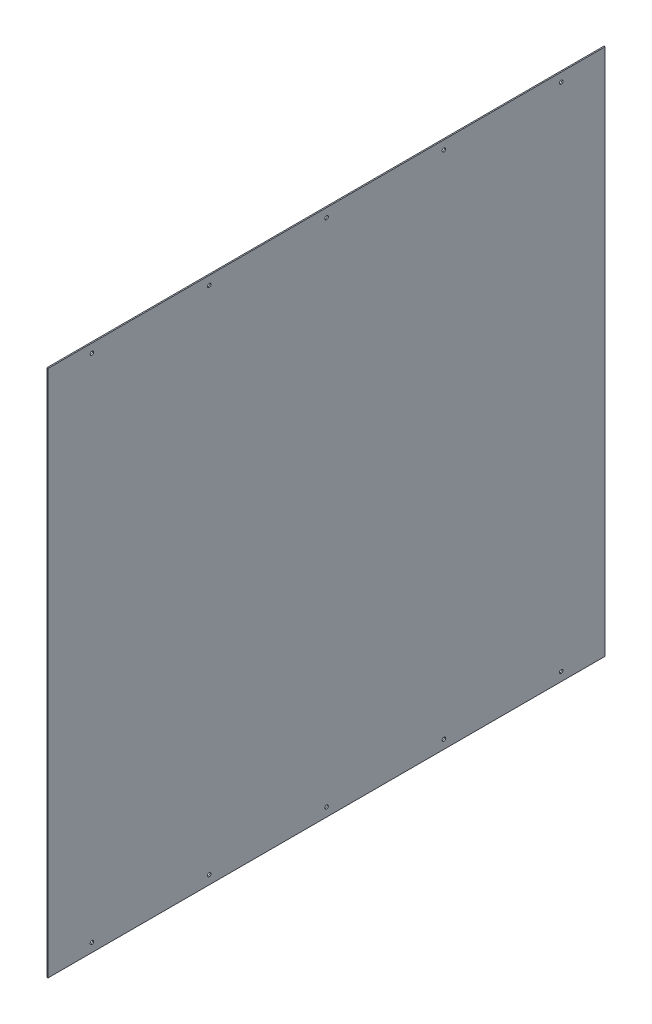
SolidWorks part; units mm, degrees
ref_plane "Front Plane" through (0, 0, 0) normal (0, 0, 1) x (1, 0, 0)
ref_plane "Top Plane" through (0, 0, 0) normal (0, 1, 0) x (1, 0, 0)
ref_plane "Right Plane" through (0, 0, 0) normal (1, 0, 0) x (0, 0, -1)
sketch "Sketch1" plane through (0, 0, 0) normal (1, 0, 0) x (0, 0, -1)
  line L1 (-475, -450) -> (475, -450)
  line L2 (-475, -450) -> (-475, 450)
  line L3 (-475, 450) -> (475, 450)
  line L4 (475, -450) -> (475, 450)
  line L5 (-475, -450) -> (475, 450) construction
  line L6 (-475, 450) -> (475, -450) construction
  point P0 (0, 0)
  dimension "D1" = 950
  dimension "D2" = 900
extrude "Boss-Extrude2" add sketch "Sketch1" along normal blind 2
sketch "Sketch3" plane through (2, 0, 0) normal (1, 0, 0) x (0, 0, -1)
  line L0 (475, 450) -> (-475, 450) construction
  line L1 (-475, 450) -> (-475, -450) construction
  line L3 (-475, 0) -> (475, 0) construction
  line L4 (475, -450) -> (475, 450) construction
  circle A0 centre (-400, 435) radius 3
  circle A1 centre (-200, 435) radius 3
  circle A2 centre (0, 435) radius 3
  circle A3 centre (200, 435) radius 3
  circle A4 centre (400, 435) radius 3
  circle A5 centre (400, -435) radius 3
  circle A6 centre (0, -435) radius 3
  circle A7 centre (200, -435) radius 3
  circle A8 centre (-200, -435) radius 3
  circle A9 centre (-400, -435) radius 3
  dimension "D1" = 6
  dimension "D2" = 15
  dimension "D3" = 75
  dimension "D4" = 5
extrude "Cut-Extrude1" cut sketch "Sketch3" against normal blind 2
